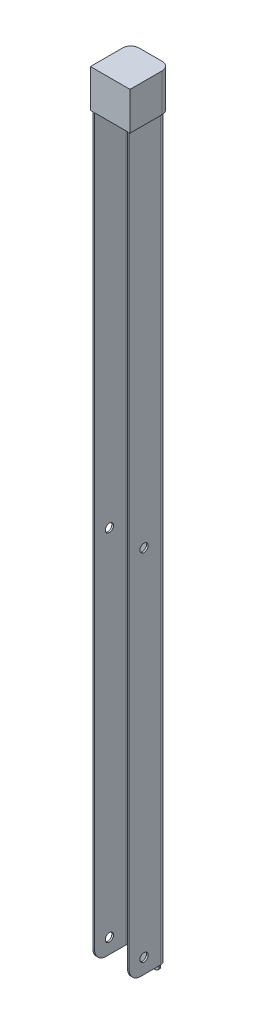
SolidWorks part; units mm, degrees
material "6063-T6"
ref_plane "Спереди" through (0, 0, 0) normal (0, 0, 1) x (1, 0, 0)
ref_plane "Сверху" through (0, 0, 0) normal (0, 1, 0) x (1, 0, 0)
ref_plane "Справа" through (0, 0, 0) normal (1, 0, 0) x (0, 0, -1)
sketch "Эскиз1" plane through (0, 0, 0) normal (0, 1, 0) x (1, 0, 0)
  line L0 (7, 11.5) -> (-7, 11.5)
  line L1 (11, 7.5) -> (11, -11.5)
  line L2 (11, -11.5) -> (-11, -11.5) construction
  line L3 (-11, 7.5) -> (-11, -11.5)
  line L4 (11, 11.5) -> (-11, -11.5) construction
  line L5 (11, -11.5) -> (-11, 11.5) construction
  arc A0 (-7, 11.5) -> (-11, 7.5) centre (-7, 7.5) ccw
  arc A1 (7, 11.5) -> (11, 7.5) centre (7, 7.5) cw
  dimension "D1" = 4
  dimension "D2" = 23
  dimension "D3" = 22
extrude "Вытянуть-Тонкостенный1" add sketch "Эскиз1" along normal blind 470 thin thin type one direction wall 1
fillet "Скругление1" radius 7 2 edges at (10.5, 0, 11.5) (-10.5, 0, 11.5)
sketch "Эскиз2" plane through (0, 470, 0) normal (0, 1, 0) x (1, 0, 0)
  line L0 (11, 7.5) -> (11, -11.5) construction
  line L1 (-7, 11.5) -> (7, 11.5) construction
  line L2 (-11, -11.5) -> (-11, 7.5) construction
  line L3 (11, 7.5) -> (11, -11.5) construction
  line L4 (-7, 11.5) -> (7, 11.5) construction
  line L5 (-11, -11.5) -> (-11, 7.5) construction
  line L6 (-12, -11.5) -> (-12, 7.5)
  line L7 (-7, 12.5) -> (7, 12.5)
  line L8 (12, 7.5) -> (12, -11.5)
  line L10 (-12, -11.5) -> (-12, -12)
  line L11 (-12, -12) -> (12, -12)
  line L12 (12, -12) -> (12, -11.5)
  arc A0 (11, 7.5) -> (7, 11.5) centre (7, 7.5) ccw construction
  arc A1 (-7, 11.5) -> (-11, 7.5) centre (-7, 7.5) ccw construction
  arc A2 (11, 7.5) -> (7, 11.5) centre (7, 7.5) ccw construction
  arc A3 (-7, 11.5) -> (-11, 7.5) centre (-7, 7.5) ccw construction
  arc A4 (-7, 12.5) -> (-12, 7.5) centre (-7, 7.5) ccw
  arc A5 (12, 7.5) -> (7, 12.5) centre (7, 7.5) ccw
  dimension "D2" = 24.5
  dimension "D1" = 1
extrude "Бобышка-Вытянуть1" add sketch "Эскиз2" against normal blind 23
sketch "Эскиз5" plane through (0, 0, -11.5) normal (0, 0, -1) x (-1, 0, 0)
  line L1 (-7, 0) -> (7, 0)
  line L2 (-7, 0) -> (-7, -7)
  line L3 (-7, -7) -> (7, -7)
  line L4 (7, 0) -> (7, -7)
  dimension "D1" = 7
extrude "Бобышка-Вытянуть2" add sketch "Эскиз5" against normal blind 1
fillet "Скругление2" radius 2 2 edges at (7, -7, -11) (-7, -7, -11)
sketch "Эскиз3" plane through (-11, 0, 0) normal (-1, 0, 0) x (0, 0, 1)
  line L0 (2.5, 9) -> (-11.5, 9) construction
  line L1 (-11.5, 447) -> (-11.5, 0) construction
  line L2 (4.5, 0) -> (-7.5, 0) construction
  line L3 (2.5, 9) -> (2.5, 224) construction
  circle A0 centre (2.5, 9) radius 2.5
  circle A1 centre (2.5, 224) radius 2.5
  dimension "D1" = 14
  dimension "D2" = 9
  dimension "D3" = 5
  dimension "D4" = 215
extrude "Вырез-Вытянуть1" cut sketch "Эскиз3" against normal through all
